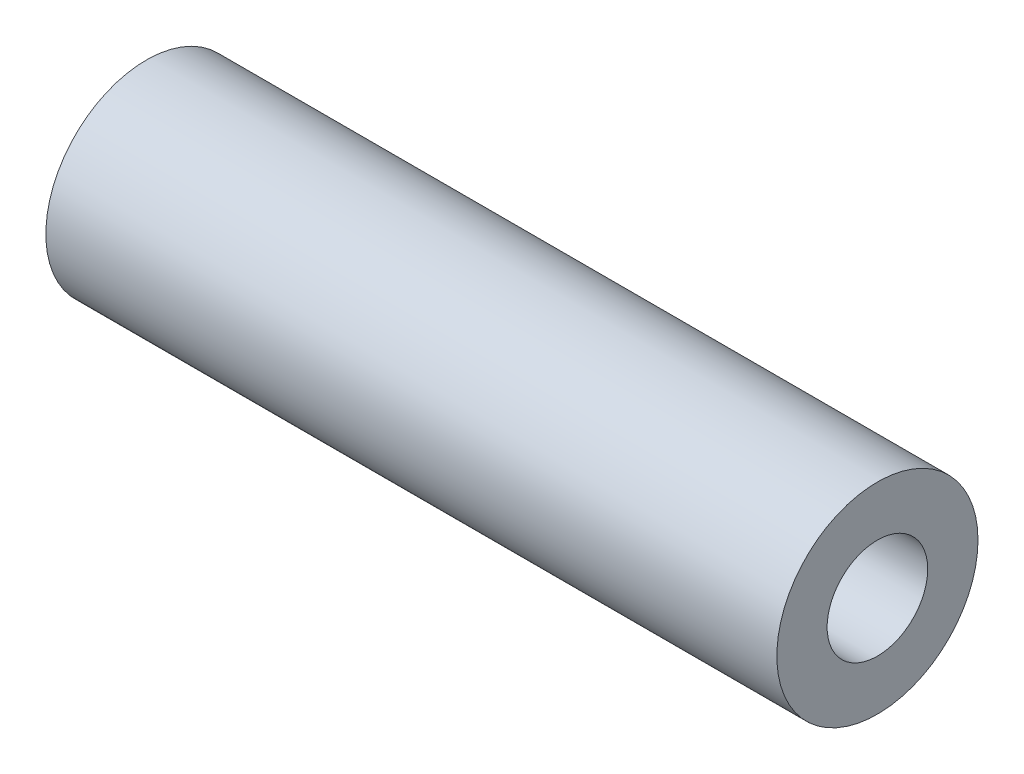
SolidWorks part; units mm, degrees
material "PVC Rigid"
ref_plane "Front Plane" through (0, 0, 0) normal (0, 0, 1) x (1, 0, 0)
ref_plane "Top Plane" through (0, 0, 0) normal (0, 1, 0) x (1, 0, 0)
ref_plane "Right Plane" through (0, 0, 0) normal (1, 0, 0) x (0, 0, -1)
sketch "Sketch1" plane through (0, 0, 0) normal (1, 0, 0) x (0, 0, -1)
  circle A0 centre (0, 0) radius 3.175
  circle A1 centre (0, 0) radius 6.35
  dimension "D1" = 6.35
  dimension "D2" = 12.7
extrude "Boss-Extrude1" add sketch "Sketch1" along normal mid plane 46.1518
